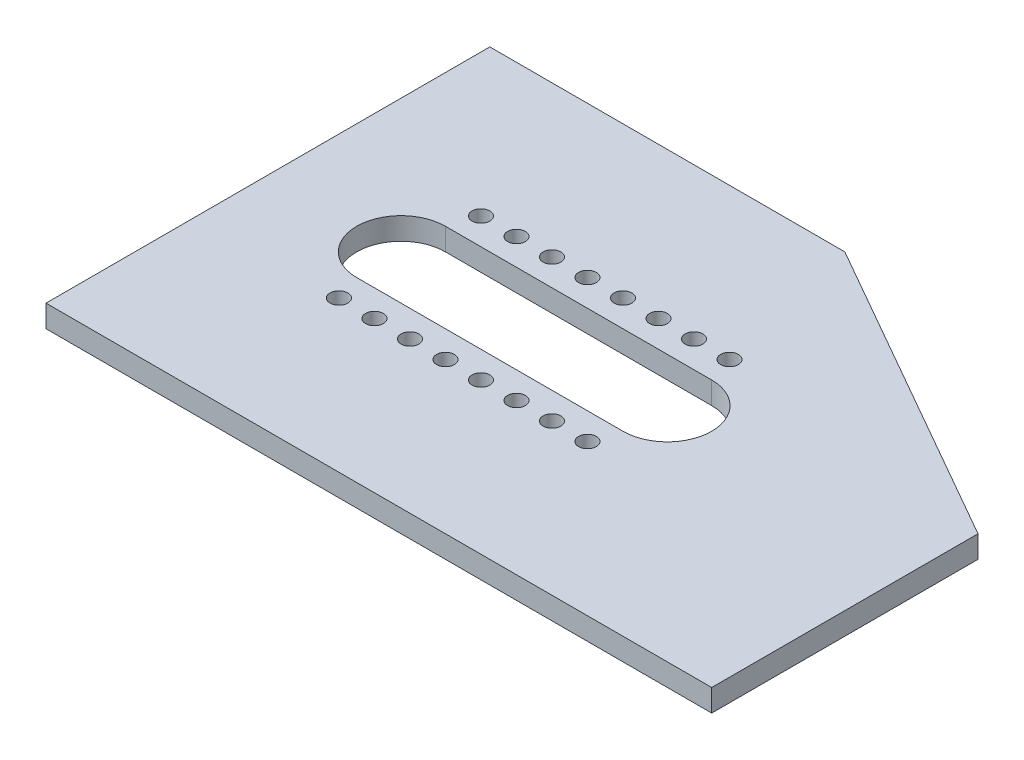
SolidWorks part; units mm, degrees
ref_plane "前视基准面" through (0, 0, 0) normal (0, 0, 1) x (1, 0, 0)
ref_plane "上视基准面" through (0, 0, 0) normal (0, 1, 0) x (1, 0, 0)
ref_plane "右视基准面" through (0, 0, 0) normal (1, 0, 0) x (0, 0, -1)
sketch "Sketch1" plane through (0, 0, 0) normal (0, 1, 0) x (1, 0, 0)
  line L0 (0, 0) -> (80, 0)
  line L1 (80, 0) -> (150, -40)
  line L2 (150, -40) -> (150, -100)
  line L3 (150, -100) -> (0, -100)
  line L4 (0, -100) -> (0, 0)
  dimension "D1" = 100
  dimension "D2" = 80
  dimension "D3" = 150
  dimension "D4" = 60
extrude "Boss-Extrude1" add sketch "Sketch1" along normal blind 5
sketch "Sketch2" plane through (0, 5, 0) normal (0, 1, 0) x (1, 0, 0)
  line L0 (0, -50) -> (157.2626, -50) construction
  line L1 (0, 0) -> (0, -100) construction
  line L2 (40, 0) -> (40, -106.8103) construction
  line L3 (80, 0) -> (0, 0) construction
  line L4 (60, 0) -> (60, -106.8103) construction
  line L5 (30, -50) -> (90, -50) construction
  line L6 (30, -40) -> (90, -40)
  line L7 (30, -60) -> (90, -60)
  arc A0 (30, -40) -> (30, -60) centre (30, -50) ccw
  arc A1 (90, -60) -> (90, -40) centre (90, -50) ccw
  circle A2 centre (32, -34) radius 2
  circle A3 centre (40, -34) radius 2
  circle A4 centre (48, -34) radius 2
  circle A5 centre (56, -34) radius 2
  circle A6 centre (64, -34) radius 2
  circle A7 centre (72, -34) radius 2
  circle A8 centre (80, -34) radius 2
  circle A9 centre (88, -34) radius 2
  circle A10 centre (88, -66) radius 2
  circle A11 centre (80, -66) radius 2
  circle A12 centre (72, -66) radius 2
  circle A13 centre (64, -66) radius 2
  circle A14 centre (56, -66) radius 2
  circle A15 centre (48, -66) radius 2
  circle A16 centre (40, -66) radius 2
  circle A17 centre (32, -66) radius 2
  point P12 (60, -50)
  dimension "D2" = 10
  dimension "D5" = 4
  dimension "D3" = 30
  dimension "D4" = 60
  dimension "D6" = 16
  dimension "D7" = 32
  dimension "D9" = 56
  dimension "D1" = 20
  dimension "D8" = 8
extrude "Cut-Extrude1" cut sketch "Sketch2" against normal through all
